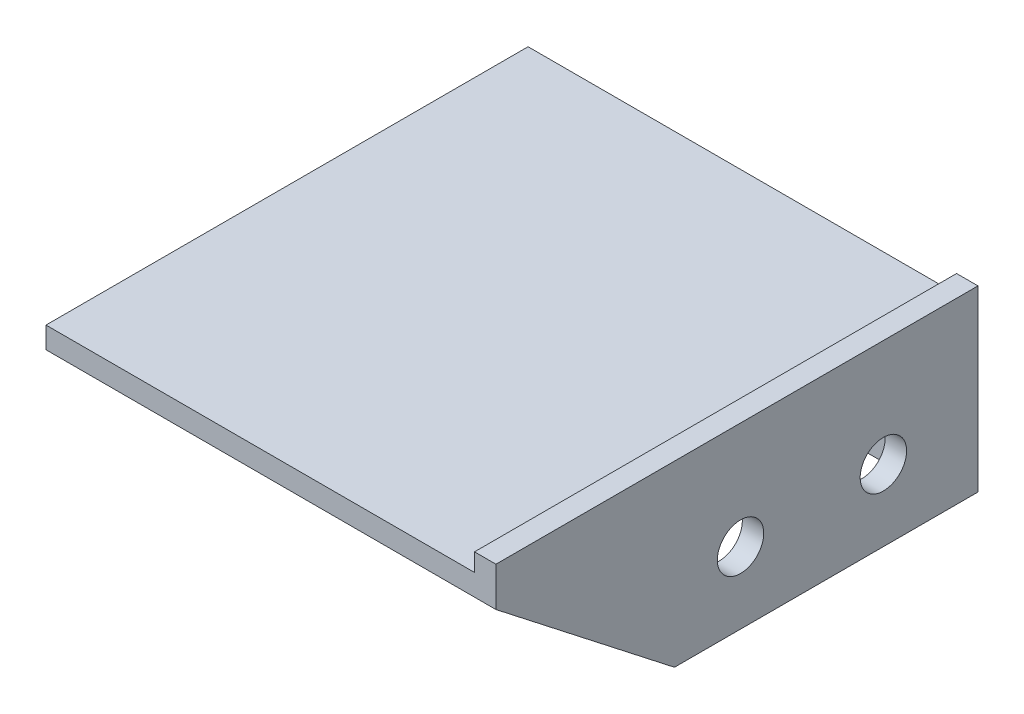
SolidWorks part; units mm, degrees
ref_plane "前视基准面" through (0, 0, 0) normal (0, 0, 1) x (1, 0, 0)
ref_plane "上视基准面" through (0, 0, 0) normal (0, 1, 0) x (1, 0, 0)
ref_plane "右视基准面" through (0, 0, 0) normal (1, 0, 0) x (0, 0, -1)
sketch "草图2" plane through (0, 0, 0) normal (0, 1, 0) x (1, 0, 0)
  line L1 (0, 0) -> (240, 0)
  line L2 (0, 0) -> (0, 270)
  line L3 (0, 270) -> (240, 270)
  line L4 (240, 0) -> (240, 270)
  dimension "D1" = 240
  dimension "D2" = 270
extrude "凸台-拉伸1" add sketch "草图2" along normal blind 12
sketch "草图3" plane through (240, 0, 0) normal (1, 0, 0) x (0, 0, -1)
  line L1 (270, 22) -> (0, 22)
  line L2 (270, 22) -> (270, -78)
  line L3 (270, -78) -> (0, -78)
  line L4 (0, 22) -> (0, -78)
  line L5 (0, 12) -> (270, 12) construction
  line L6 (0, 12) -> (0, 0) construction
  line L7 (270, 12) -> (270, 0) construction
  dimension "D1" = 100
  dimension "D2" = 10
extrude "凸台-拉伸2" add sketch "草图3" along normal blind 12
sketch "草图4" plane through (240, 0, 0) normal (-1, 0, 0) x (0, 0, 1)
  line L0 (0, 0) -> (-270, 0) construction
  line L1 (-270, -78) -> (-258, -78)
  line L2 (-270, -78) -> (-270, 0)
  line L3 (-270, 0) -> (-258, 0)
  line L4 (-258, -78) -> (-258, 0)
  dimension "D1" = 12
extrude "凸台-拉伸3" add sketch "草图4" along normal blind 240
sketch "草图5" plane through (0, 0, -258) normal (0, 0, 1) x (1, 0, 0)
  line L0 (-969.0039, -38) -> (49030.9961, -38) construction
  line L1 (0, -78) -> (0, 0) construction
  line L2 (0, -78) -> (240, -78) construction
  circle A0 centre (38, -38) radius 13
  circle A1 centre (158, -38) radius 13
  dimension "D1" = 26
  dimension "D2" = 38
  dimension "D3" = 120
  dimension "D4" = 40
extrude "切除-拉伸1" cut sketch "草图5" against normal through all
sketch "草图6" plane through (252, 0, 0) normal (1, 0, 0) x (0, 0, -1)
  line L0 (-937.6543, -38) -> (49062.3457, -38) construction
  line L1 (0, -78) -> (270, -78) construction
  line L2 (270, -78) -> (270, 22) construction
  line L3 (0, 0) -> (100, -78)
  line L4 (100, -78) -> (0, -78)
  line L5 (0, -78) -> (0, 0)
  circle A0 centre (137, -38) radius 13
  circle A1 centre (217, -38) radius 13
  dimension "D5" = 26
  dimension "D1" = 40
  dimension "D2" = 80
  dimension "D3" = 53
  dimension "D4" = 37
extrude "切除-拉伸2" cut sketch "草图6" against normal through all
